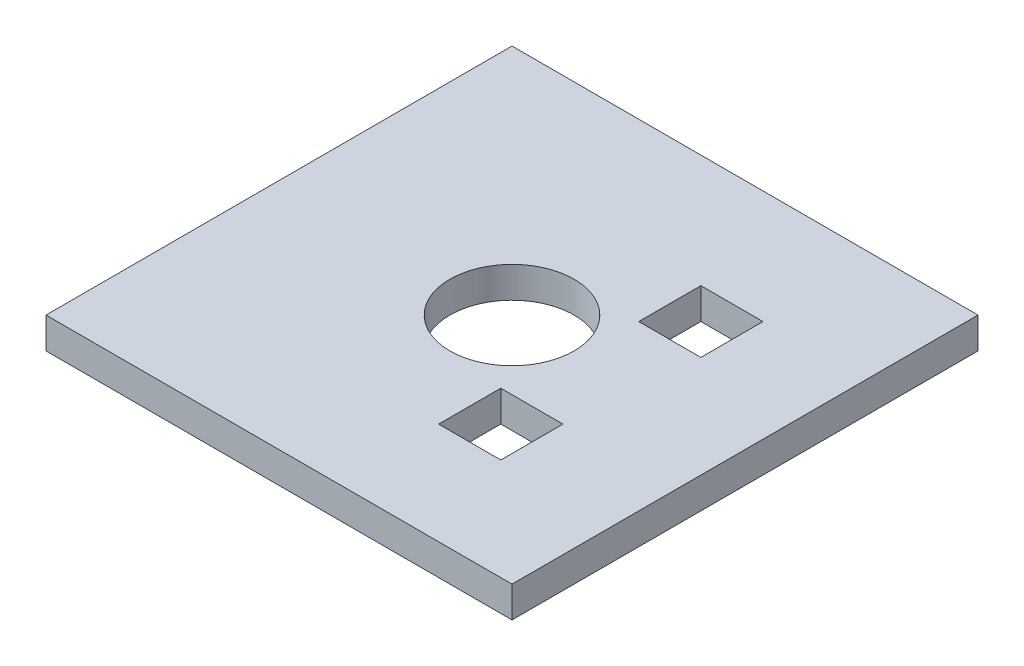
SolidWorks part; units mm, degrees
ref_plane "Front Plane" through (0, 0, 0) normal (0, 0, 1) x (1, 0, 0)
ref_plane "Top Plane" through (0, 0, 0) normal (0, 1, 0) x (1, 0, 0)
ref_plane "Right Plane" through (0, 0, 0) normal (1, 0, 0) x (0, 0, -1)
sketch "Sketch2" plane through (0, 0, 0) normal (0, 1, 0) x (1, 0, 0)
  line L1 (-75, -75) -> (75, -75)
  line L2 (-75, -75) -> (-75, 75)
  line L3 (-75, 75) -> (75, 75)
  line L4 (75, -75) -> (75, 75)
  line L5 (-75, -75) -> (75, 75) construction
  line L6 (-75, 75) -> (75, -75) construction
  circle A0 centre (0, 0) radius 20
  point P0 (0, 0)
  dimension "D2" = 40
  dimension "D1" = 150
extrude "Boss-Extrude3" add sketch "Sketch2" along normal blind 10
sketch "Sketch4" plane through (0, 10, 0) normal (0, 1, 0) x (1, 0, 0)
  line L7 (22.2049, 38.5873) -> (42.2049, 18.5873) construction
  line L8 (42.2049, 38.5873) -> (22.2049, 18.5873) construction
  line L9 (42.2049, 18.5873) -> (22.2049, 18.5873)
  line L10 (22.2049, 38.5873) -> (22.2049, 18.5873)
  line L11 (42.2049, 38.5873) -> (22.2049, 38.5873)
  line L12 (42.2049, 38.5873) -> (42.2049, 18.5873)
  line L15 (38.5873, -22.2049) -> (18.5873, -42.2049) construction
  line L16 (38.5873, -42.2049) -> (18.5873, -22.2049) construction
  line L17 (18.5873, -42.2049) -> (18.5873, -22.2049)
  line L18 (38.5873, -22.2049) -> (18.5873, -22.2049)
  line L19 (38.5873, -42.2049) -> (38.5873, -22.2049)
  line L20 (38.5873, -42.2049) -> (18.5873, -42.2049)
  point P13 (32.2049, 28.5873)
  point P20 (28.5873, -32.2049)
extrude "Cut-Extrude1" cut sketch "Sketch4" against normal blind 10
